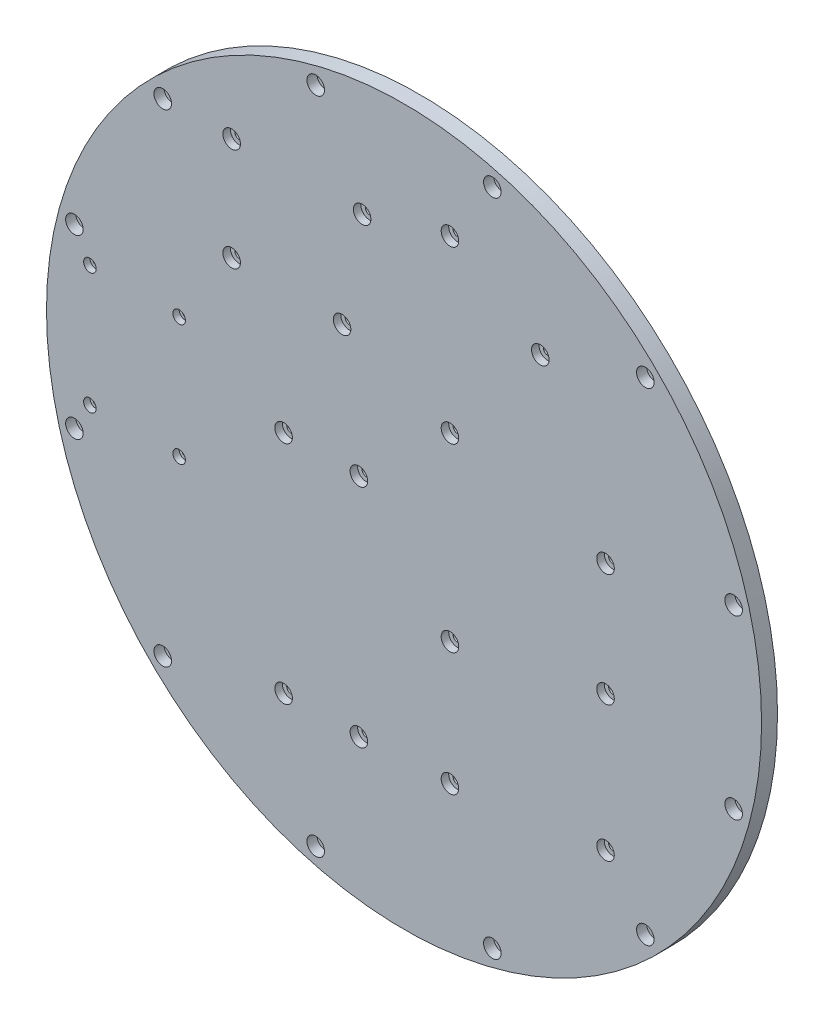
SolidWorks part; units mm, degrees
ref_plane "Plan de face" through (0, 0, 0) normal (0, 0, 1) x (1, 0, 0)
ref_plane "Plan de dessus" through (0, 0, 0) normal (0, 1, 0) x (1, 0, 0)
ref_plane "Plan de droite" through (0, 0, 0) normal (1, 0, 0) x (0, 0, -1)
sketch "Esquisse1" plane through (0, 0, 0) normal (0, 0, 1) x (1, 0, 0)
  line L0 (0, 0) -> (0, 136) construction
  line L1 (0, 0) -> (-35.1994, 131.3659) construction
  circle A3 centre (0, 0) radius 136 construction
  circle A14 centre (-35.1994, 131.3659) radius 1.75
  circle A41 centre (0, 0) radius 142.5
  circle A42 centre (35.1994, 131.3659) radius 1.75
  circle A43 centre (96.1665, 96.1665) radius 1.75
  circle A44 centre (131.3659, 35.1994) radius 1.75
  circle A45 centre (131.3659, -35.1994) radius 1.75
  circle A46 centre (96.1665, -96.1665) radius 1.75
  circle A47 centre (35.1994, -131.3659) radius 1.75
  circle A48 centre (-35.1994, -131.3659) radius 1.75
  circle A49 centre (-96.1665, -96.1665) radius 1.75
  circle A50 centre (-131.3659, -35.1994) radius 1.75
  circle A51 centre (-131.3659, 35.1994) radius 1.75
  circle A52 centre (-96.1665, 96.1665) radius 1.75
  point P31 (0, 0)
  point P34 (0, 0)
  point P41 (0, 0)
  dimension "D1" = 272
  dimension "D3" = 3.5
  dimension "D4" = 285
  dimension "D2" = 15
extrude "Boss.-Extru.1" add sketch "Esquisse1" along normal blind 6.35
sketch "Esquisse2" plane through (0, 0, 6.35) normal (0, 0, 1) x (1, 0, 0)
  circle A12 centre (35.1994, 131.3659) radius 3.5
  circle A13 centre (96.1665, 96.1665) radius 3.5
  circle A14 centre (131.3659, 35.1994) radius 3.5
  circle A15 centre (131.3659, -35.1994) radius 3.5
  circle A16 centre (96.1665, -96.1665) radius 3.5
  circle A17 centre (35.1994, -131.3659) radius 3.5
  circle A18 centre (-35.1994, -131.3659) radius 3.5
  circle A19 centre (-96.1665, -96.1665) radius 3.5
  circle A20 centre (-131.3659, -35.1994) radius 3.5
  circle A21 centre (-131.3659, 35.1994) radius 3.5
  circle A22 centre (-96.1665, 96.1665) radius 3.5
  circle A23 centre (-35.1994, 131.3659) radius 3.5
  point P20 (0, 0)
  point P27 (0, 0)
  dimension "D1" = 7
extrude "Enlèv. mat.-Extru.1" cut sketch "Esquisse2" against normal blind 4
sketch "Esquisse3" plane through (0, 0, 6.35) normal (0, 0, 1) x (1, 0, 0)
  line L0 (-125.1958, -24.13) -> (-125.1958, 24.13) construction
  line L1 (-125.1958, 24.13) -> (-89.6358, 24.13) construction
  line L2 (-89.6358, 24.13) -> (-89.6358, -24.13) construction
  line L3 (-89.6358, -24.13) -> (-125.1958, -24.13) construction
  circle A0 centre (0, 0) radius 127.5 construction
  circle A3 centre (-125.1958, -24.13) radius 1.25
  circle A4 centre (-125.1958, 24.13) radius 1.25
  circle A5 centre (-89.6358, 24.13) radius 1.25
  circle A6 centre (-89.6358, -24.13) radius 1.25
  dimension "D1" = 255
  dimension "D2" = 35.56
  dimension "D4" = 2.5
  dimension "D3" = 48.26
extrude "Enlèv. mat.-Extru.2" cut sketch "Esquisse3" against normal up to next
sketch "Esquisse4" plane through (0, 0, 6.35) normal (0, 0, 1) x (1, 0, 0)
  circle A0 centre (-125.1958, -24.13) radius 2.5
  circle A1 centre (-125.1958, 24.13) radius 2.5
  circle A2 centre (-89.6358, 24.13) radius 2.5
  circle A3 centre (-89.6358, -24.13) radius 2.5
  dimension "D1" = 5
extrude "Enlèv. mat.-Extru.3" cut sketch "Esquisse4" against normal blind 2.5
sketch "Esquisse5" plane through (0, 0, 6.35) normal (0, 0, 1) x (1, 0, 0)
  circle A0 centre (-48, -85) radius 1.75
  circle A1 centre (-48, 5) radius 1.75
  circle A2 centre (-18, 5) radius 1.75
  circle A3 centre (-18, -85) radius 1.75
  circle A4 centre (0, 0) radius 142.5 construction
  circle A5 centre (0, 0) radius 142.5 construction
  dimension "D4" = 3.5
  dimension "D1" = 90
  dimension "D2" = 30
  dimension "D3" = 5
  dimension "D5" = 18
extrude "Enlèv. mat.-Extru.4" cut sketch "Esquisse5" against normal up to next
sketch "Esquisse6" plane through (0, 0, 6.35) normal (0, 0, 1) x (1, 0, 0)
  circle A0 centre (-48, -85) radius 3.5
  circle A1 centre (-18, -85) radius 3.5
  circle A2 centre (-48, 5) radius 3.5
  circle A3 centre (-18, 5) radius 3.5
  dimension "D1" = 7
extrude "Enlèv. mat.-Extru.5" cut sketch "Esquisse6" against normal blind 3
sketch "Esquisse7" plane through (0, 0, 6.35) normal (0, 0, 1) x (1, 0, 0)
  circle A0 centre (-68.7, 55) radius 1.75
  circle A1 centre (-68.7, 96) radius 1.75
  circle A2 centre (-24.7, 54) radius 1.75
  circle A3 centre (-16.7, 96) radius 1.75
  circle A5 centre (-18, 5) radius 3.5 construction
  circle A7 centre (-48, 5) radius 3.5 construction
  circle A8 centre (-18, 5) radius 3.5 construction
  circle A9 centre (-48, 5) radius 3.5 construction
  point P14 (0, 0)
  point P15 (0, 0)
  dimension "D5" = 3.5
  dimension "D7" = 50
  dimension "D1" = 44
  dimension "D2" = 41
  dimension "D3" = 42
  dimension "D4" = 52
  dimension "D6" = 6.7
extrude "Enlèv. mat.-Extru.6" cut sketch "Esquisse7" against normal up to next
sketch "Esquisse8" plane through (0, 0, 6.35) normal (0, 0, 1) x (1, 0, 0)
  circle A0 centre (-68.7, 55) radius 3.5
  circle A1 centre (-68.7, 96) radius 3.5
  circle A2 centre (-24.7, 54) radius 3.5
  circle A3 centre (-16.7, 96) radius 3.5
  dimension "D1" = 7
extrude "Enlèv. mat.-Extru.7" cut sketch "Esquisse8" against normal blind 3
sketch "Esquisse9" plane through (0, 0, 6.35) normal (0, 0, -1) x (-1, 0, 0)
  circle A0 centre (-18.3, 106) radius 1.75
  circle A1 centre (-18.3, 38) radius 1.75
  circle A2 centre (-54.3, 83) radius 1.75
  circle A3 centre (-80.3, 24) radius 1.75
  circle A6 centre (16.7, 96) radius 1.75 construction
  circle A7 centre (16.7, 96) radius 1.75 construction
  point P11 (0, 0)
  point P12 (0, 0)
  dimension "D1" = 3.5
  dimension "D2" = 68
  dimension "D3" = 23
  dimension "D4" = 36
  dimension "D5" = 62
  dimension "D6" = 35
  dimension "D7" = 82
  dimension "D8" = 10
extrude "Enlèv. mat.-Extru.8" cut sketch "Esquisse9" along normal up to next
sketch "Esquisse10" plane through (0, 0, 6.35) normal (0, 0, 1) x (1, 0, 0)
  circle A0 centre (18.3, 38) radius 3.5
  circle A1 centre (18.3, 106) radius 3.5
  circle A2 centre (54.3, 83) radius 3.5
  circle A3 centre (80.3, 24) radius 3.5
  dimension "D1" = 7
extrude "Enlèv. mat.-Extru.9" cut sketch "Esquisse10" against normal blind 3
sketch "Esquisse11" plane through (0, 0, 6.35) normal (0, 0, -1) x (-1, 0, 0)
  circle A0 centre (-18.3, -34) radius 1.75
  circle A1 centre (-18.3, -83) radius 1.75
  circle A2 centre (-80.3, -21) radius 1.75
  circle A3 centre (-80.3, -75) radius 1.75
  circle A7 centre (-18.3, 38) radius 1.75 construction
  circle A8 centre (-18.3, 38) radius 1.75 construction
  point P11 (0, 0)
  dimension "D1" = 3.5
  dimension "D2" = 49
  dimension "D6" = 59
  dimension "D3" = 62
  dimension "D4" = 13
  dimension "D5" = 54
extrude "Enlèv. mat.-Extru.10" cut sketch "Esquisse11" along normal up to next
sketch "Esquisse12" plane through (0, 0, 6.35) normal (0, 0, 1) x (1, 0, 0)
  circle A0 centre (18.3, -83) radius 3.5
  circle A1 centre (18.3, -34) radius 3.5
  circle A2 centre (80.3, -21) radius 3.5
  circle A3 centre (80.3, -75) radius 3.5
  dimension "D1" = 7
extrude "Enlèv. mat.-Extru.11" cut sketch "Esquisse12" against normal blind 3
